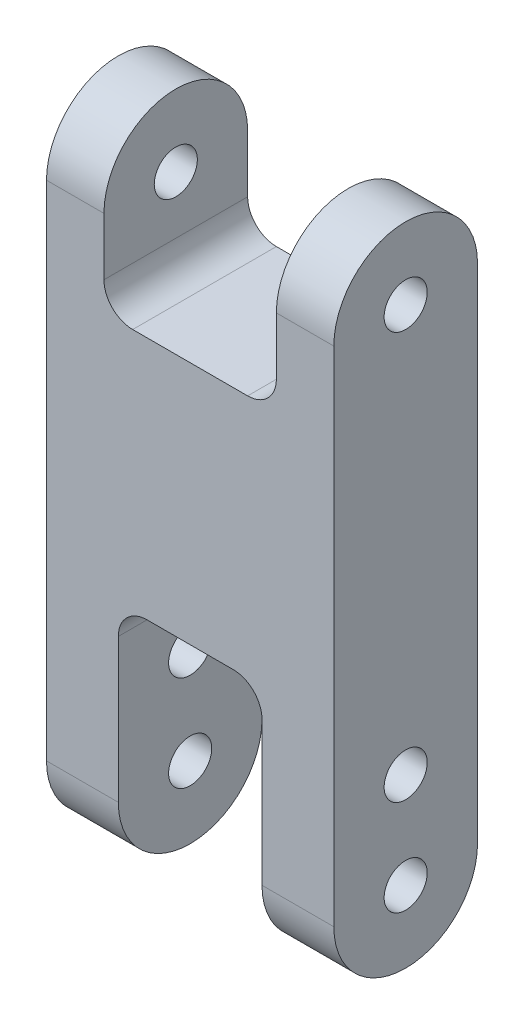
SolidWorks part; units mm, degrees
material "ABS"
ref_plane "Plan de face" through (0, 0, 0) normal (0, 0, 1) x (1, 0, 0)
ref_plane "Plan de dessus" through (0, 0, 0) normal (0, 1, 0) x (1, 0, 0)
ref_plane "Plan de droite" through (0, 0, 0) normal (1, 0, 0) x (0, 0, -1)
sketch "Esquisse1" plane through (0, 0, 0) normal (0, 0, 1) x (1, 0, 0)
  line L0 (0.4815, 8.1448) -> (-7.5185, 8.1448)
  line L1 (-9.5185, 10.1448) -> (-9.5185, 19.1448)
  line L2 (-9.5185, 19.1448) -> (-13.5185, 19.1448)
  line L3 (-13.5185, 19.1448) -> (-13.5185, -25.8552)
  line L4 (-13.5185, -25.8552) -> (-8.5185, -25.8552)
  line L5 (-8.5185, -25.8552) -> (-8.5185, -10.8552)
  line L6 (-6.5185, -8.8552) -> (-0.5185, -8.8552)
  line L7 (-3.5185, 8.1448) -> (-3.5185, -8.8552) construction
  line L8 (1.4815, -25.8552) -> (1.4815, -10.8552)
  line L9 (6.4815, -25.8552) -> (1.4815, -25.8552)
  line L10 (6.4815, 19.1448) -> (6.4815, -25.8552)
  line L11 (2.4815, 19.1448) -> (6.4815, 19.1448)
  line L12 (2.4815, 10.1448) -> (2.4815, 19.1448)
  arc A0 (-8.5185, -10.8552) -> (-6.5185, -8.8552) centre (-6.5185, -10.8552) cw
  arc A1 (1.4815, -10.8552) -> (-0.5185, -8.8552) centre (-0.5185, -10.8552) ccw
  arc A2 (2.4815, 10.1448) -> (0.4815, 8.1448) centre (0.4815, 10.1448) cw
  arc A3 (-7.5185, 8.1448) -> (-9.5185, 10.1448) centre (-7.5185, 10.1448) cw
  point P16 (-8.5185, -8.8552)
  point P19 (1.4815, -8.8552)
  point P22 (2.4815, 8.1448)
  point P25 (-9.5185, 8.1448)
  dimension "D7" = 2
  dimension "D1" = 45
  dimension "D2" = 6
  dimension "D3" = 5
  dimension "D4" = 11
  dimension "D5" = 17
  dimension "D6" = 5
extrude "Boss.-Extru.1" add sketch "Esquisse1" along normal blind 10 contours L3 L4 L5 A0 L6 A1 L8 L9 L10 L11 L12 A2 L0 A3 L1 L2
sketch "Esquisse2" plane through (-13.5185, 0, 0) normal (-1, 0, 0) x (0, 0, 1)
  line L0 (0, 14.1448) -> (0, 19.1448)
  line L2 (0, 19.1448) -> (10, 19.1448)
  line L3 (10, 19.1448) -> (10, 14.1448)
  line L5 (10, 19.1448) -> (10, -25.8552) construction
  line L6 (0, -20.8552) -> (0, -25.8552)
  line L8 (0, -25.8552) -> (10, -25.8552)
  line L9 (10, -25.8552) -> (10, -20.8552)
  arc A0 (0, 14.1448) -> (10, 14.1448) centre (5, 14.1448) cw
  arc A1 (0, -20.8552) -> (10, -20.8552) centre (5, -20.8552) ccw
  circle A2 centre (5, -20.8552) radius 1.5
  circle A3 centre (5, 14.1448) radius 1.5
  circle A4 centre (5, -14.1952) radius 1.5
  point P2 (5, 19.1448)
  point P12 (5, -25.8552)
  line M4 (0, 19.1448) -> (0, -25.8552)
  line M5 (0, -25.8552) -> (10, -25.8552)
  line M6 (10, -25.8552) -> (10, 19.1448)
  line M7 (10, 19.1448) -> (0, 19.1448)
  dimension "D1" = 3
  dimension "D2" = 3
  dimension "D3" = 3
  dimension "D4" = 6.66
extrude "Enlèv. mat.-Extru.1" cut sketch "Esquisse2" against normal through all contours A1 L8 M6 | A1 M4 M5 | A2 | A0 M7 M6 | A0 L2 M4 | A3 | A4
